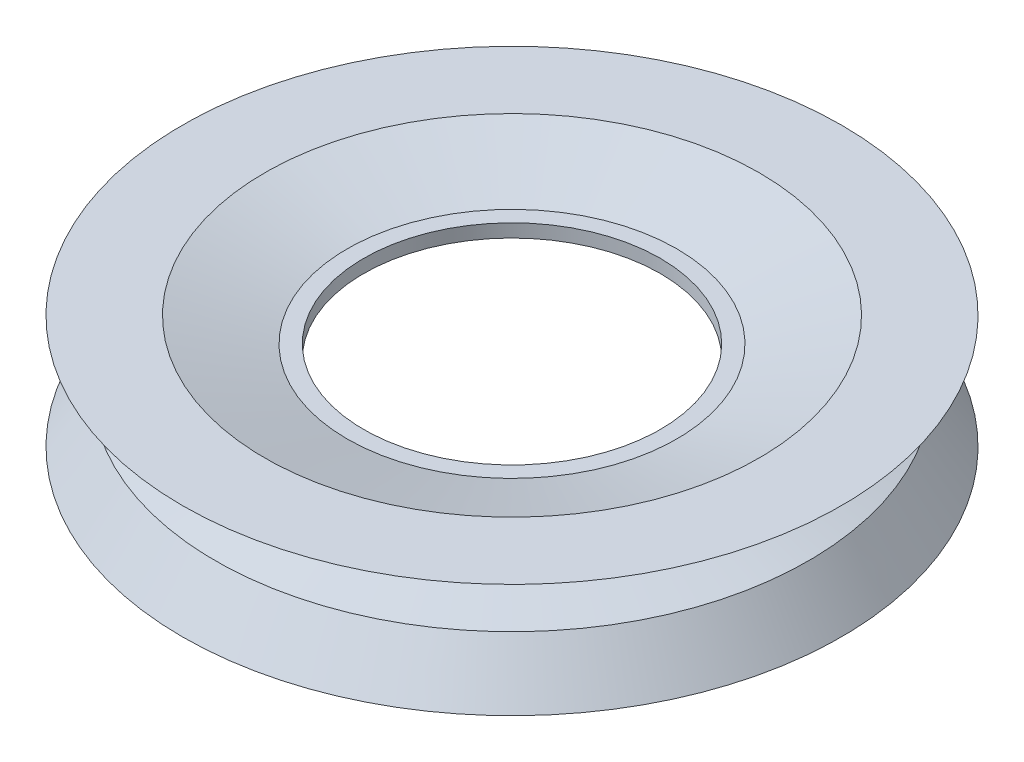
SolidWorks part; units mm, degrees
material "Caoutchouc"
ref_plane "Plan de face" through (0, 0, 0) normal (0, 0, 1) x (1, 0, 0)
ref_plane "Plan de dessus" through (0, 0, 0) normal (0, 1, 0) x (1, 0, 0)
ref_plane "Plan de droite" through (0, 0, 0) normal (1, 0, 0) x (0, 0, -1)
sketch "Esquisse1" plane through (0, 0, 0) normal (0, 0, 1) x (1, 0, 0)
  line L0 (0, 0) -> (0, 54.9782) construction
  line L1 (8.5, 0) -> (10, 0)
  line L2 (10, 0) -> (9, 1.5)
  line L3 (9, 1.5) -> (6, 2.5)
  line L4 (5, 2.7) -> (7.5, 3.45)
  line L5 (7.5, 3.45) -> (10, 3.45)
  line L6 (10, 3.45) -> (6, 2.5)
  line L7 (5, 2.7) -> (4.5, 2.7)
  line L8 (4.5, 2.7) -> (4.5, 2.3)
  line L9 (4.5, 2.3) -> (8.5, 0.8)
  line L10 (8.5, 0.8) -> (8.5, 0)
  dimension "D1" = 9
  dimension "D2" = 5
  dimension "D3" = 10
  dimension "D4" = 8.5
  dimension "D5" = 6
  dimension "D6" = 9
  dimension "D7" = 10
  dimension "D8" = 7.5
  dimension "D9" = 0.95
  dimension "D11" = 1.5
  dimension "D12" = 0.8
  dimension "D13" = 1.5
  dimension "D14" = 1
revolve "Révolution1" add sketch "Esquisse1" angle 360 about L0
